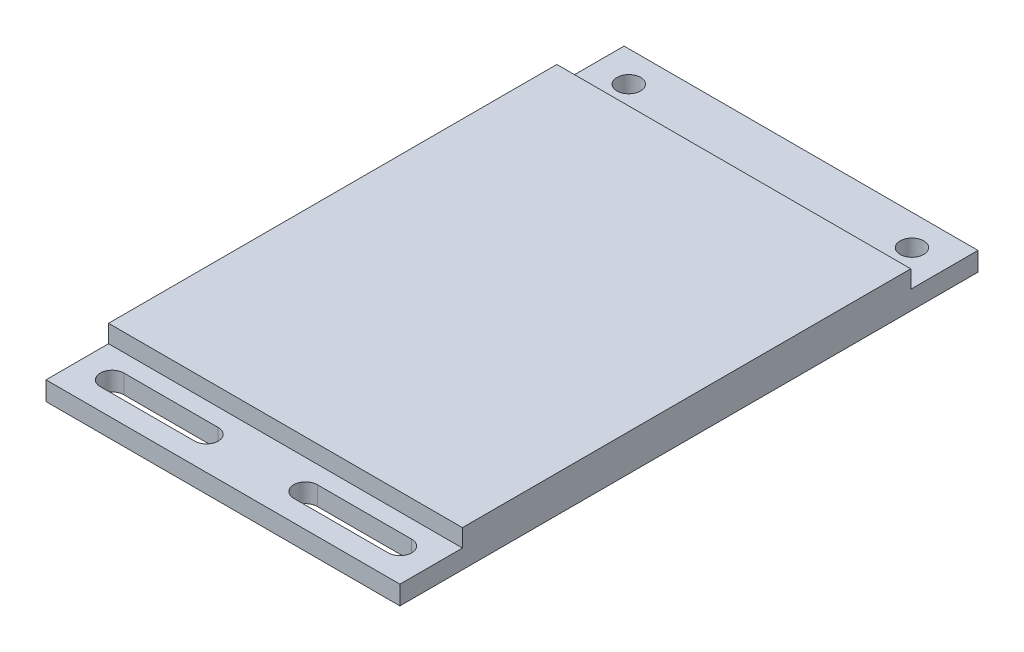
SolidWorks part; units mm, degrees
ref_plane "前视基准面" through (0, 0, 0) normal (0, 0, 1) x (1, 0, 0)
ref_plane "上视基准面" through (0, 0, 0) normal (0, 1, 0) x (1, 0, 0)
ref_plane "右视基准面" through (0, 0, 0) normal (1, 0, 0) x (0, 0, -1)
sketch "草图1" plane through (0, 0, 0) normal (0, 1, 0) x (1, 0, 0)
  line L0 (0, -2.6) -> (30, -2.6) construction
  line L1 (0, 0) -> (30, 0)
  line L2 (0, 0) -> (0, -49)
  line L3 (0, -49) -> (30, -49)
  line L4 (30, 0) -> (30, -49)
  line L5 (0, -46.2) -> (30, -46.2) construction
  line L7 (2.8, -45.2) -> (10.8, -45.2)
  line L8 (2.8, -45.2) -> (2.8, -47.2)
  line L9 (2.8, -47.2) -> (10.8, -47.2)
  line L10 (10.8, -45.2) -> (10.8, -47.2)
  line L11 (19.2, -45.2) -> (27.2, -45.2)
  line L12 (19.2, -45.2) -> (19.2, -47.2)
  line L13 (19.2, -47.2) -> (27.2, -47.2)
  line L14 (27.2, -45.2) -> (27.2, -47.2)
  circle A0 centre (3, -2.6) radius 1
  circle A1 centre (27, -2.6) radius 1
  circle A2 centre (2.8, -46.2) radius 1
  circle A3 centre (10.8, -46.2) radius 1
  circle A4 centre (27.2, -46.2) radius 1
  circle A5 centre (19.2, -46.2) radius 1
  dimension "D4" = 2
  dimension "D5" = 2
  dimension "D13" = 2
  dimension "D14" = 2
  dimension "D15" = 2
  dimension "D16" = 2
  dimension "D1" = 49
  dimension "D2" = 30
  dimension "D3" = 2.6
  dimension "D6" = 3
  dimension "D7" = 3
  dimension "D8" = 2.8
  dimension "D9" = 2.8
  dimension "D10" = 2.8
  dimension "D11" = 8
  dimension "D12" = 8
extrude "凸台-拉伸1" add sketch "草图1" along normal blind 1.6 contours L4 L1 L2 L3 A5 L11 A4 L13 A3 L9 A2 L7 A1 A0
sketch "草图2" plane through (0, 1.6, 0) normal (0, 1, 0) x (1, 0, 0)
  line L0 (0, 0) -> (0, -49) construction
  line L1 (0, -5.7) -> (30, -5.7)
  line L2 (0, -5.7) -> (0, -43.7)
  line L3 (0, -43.7) -> (30, -43.7)
  line L4 (30, -5.7) -> (30, -43.7)
  line L5 (30, 0) -> (30, -49) construction
  line L6 (0, -49) -> (30, -49) construction
  dimension "D1" = 5.3
  dimension "D2" = 38
extrude "凸台-拉伸2" add sketch "草图2" along normal blind 1.5
sketch "草图3" plane through (0, 0, 0) normal (0, -1, 0) x (1, 0, 0)
  line L0 (30, 0) -> (30, 49) construction
  line L1 (19.2, 40.5) -> (10.8, 40.5)
  line L2 (19.2, 40.5) -> (19.2, 35.5)
  line L3 (19.2, 35.5) -> (10.8, 35.5)
  line L4 (10.8, 40.5) -> (10.8, 35.5)
  line L5 (0, 49) -> (30, 49) construction
  dimension "D1" = 10.8
  dimension "D2" = 8.5
  dimension "D3" = 8.4
  dimension "D4" = 5
extrude "凸台-拉伸3" add sketch "草图3" along normal blind 2
